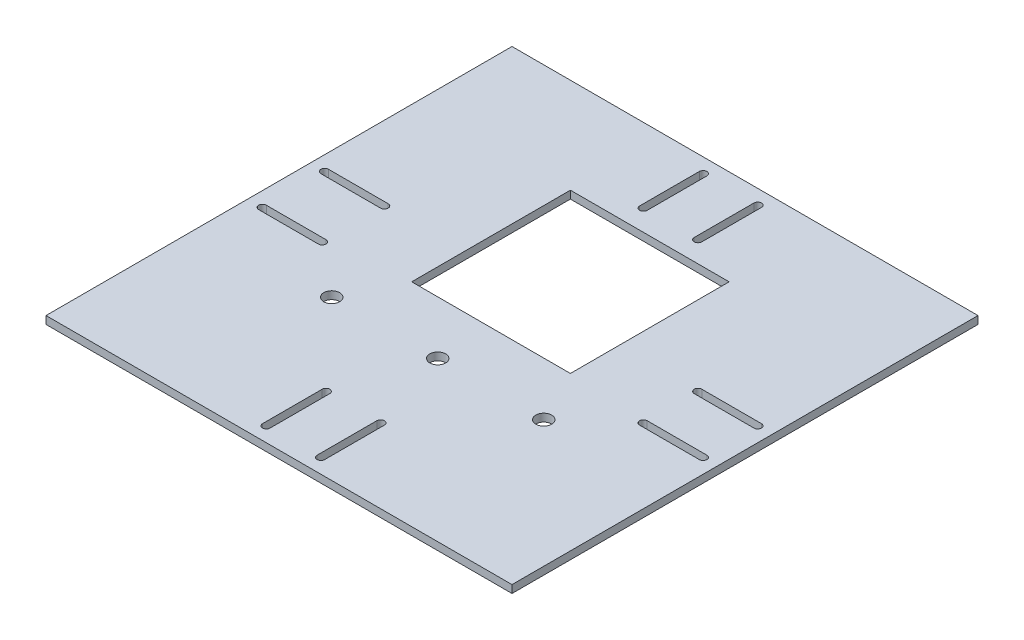
SolidWorks part; units mm, degrees
material "Acrylic (Medium-high impact)"
ref_plane "Front Plane" through (0, 0, 0) normal (0, 0, 1) x (1, 0, 0)
ref_plane "Top Plane" through (0, 0, 0) normal (0, 1, 0) x (1, 0, 0)
ref_plane "Right Plane" through (0, 0, 0) normal (1, 0, 0) x (0, 0, -1)
sketch "Sketch3" plane through (0, 0, 0) normal (0, 1, 0) x (1, 0, 0)
  line L1 (0, 0) -> (186.436, 0)
  line L2 (0, 0) -> (0, 186.436)
  line L3 (0, 186.436) -> (186.436, 186.436)
  line L4 (186.436, 0) -> (186.436, 186.436)
  dimension "D1" = 186.436
  dimension "D2" = 186.436
extrude "Boss-Extrude1" add sketch "Sketch3" along normal blind 3.0988
sketch "Sketch4" plane through (0, 3.0988, 0) normal (0, 1, 0) x (1, 0, 0)
  line L0 (5.842, 80.772) -> (29.718, 80.772) construction
  line L1 (5.842, 105.664) -> (29.718, 105.664) construction
  line L2 (5.842, 80.772) -> (5.842, 105.664) construction
  line L3 (29.718, 105.664) -> (29.718, 80.772) construction
  line L4 (0, 186.436) -> (0, 0) construction
  line L5 (0, 0) -> (186.436, 0) construction
  line L6 (186.436, 186.436) -> (0, 186.436) construction
  line L7 (5.842, 82.296) -> (29.718, 82.296)
  line L8 (5.842, 79.248) -> (29.718, 79.248)
  line L9 (5.842, 104.14) -> (29.718, 104.14)
  line L10 (5.842, 107.188) -> (29.718, 107.188)
  line L11 (186.436, 0) -> (186.436, 186.436) construction
  line L12 (82.296, 5.842) -> (82.296, 29.718) construction
  line L13 (82.296, 29.718) -> (104.14, 29.718) construction
  line L14 (104.14, 29.718) -> (104.14, 5.842) construction
  line L15 (104.14, 5.842) -> (82.296, 5.842) construction
  line L16 (80.772, 29.718) -> (80.772, 5.842)
  line L17 (83.82, 5.842) -> (83.82, 29.718)
  line L18 (105.664, 5.842) -> (105.664, 29.718)
  line L19 (156.718, 82.296) -> (180.594, 82.296) construction
  line L20 (156.718, 104.14) -> (180.594, 104.14) construction
  line L21 (156.718, 82.296) -> (156.718, 104.14) construction
  line L22 (180.594, 104.14) -> (180.594, 82.296) construction
  line L23 (156.718, 83.82) -> (180.594, 83.82)
  line L24 (156.718, 80.772) -> (180.594, 80.772)
  line L25 (156.718, 102.616) -> (180.594, 102.616)
  line L26 (156.718, 105.664) -> (180.594, 105.664)
  line L27 (102.616, 29.718) -> (102.616, 5.842)
  line L28 (82.296, 156.718) -> (82.296, 180.594) construction
  line L29 (82.296, 180.594) -> (104.14, 180.594) construction
  line L30 (104.14, 180.594) -> (104.14, 156.718) construction
  line L31 (104.14, 156.718) -> (82.296, 156.718) construction
  line L32 (80.772, 180.594) -> (80.772, 156.718)
  line L33 (83.82, 156.718) -> (83.82, 180.594)
  line L34 (105.664, 156.718) -> (105.664, 180.594)
  line L35 (102.616, 180.594) -> (102.616, 156.718)
  arc A0 (5.842, 82.296) -> (5.842, 79.248) centre (5.842, 80.772) ccw
  arc A1 (5.842, 107.188) -> (5.842, 104.14) centre (5.842, 105.664) ccw
  arc A2 (29.718, 104.14) -> (29.718, 107.188) centre (29.718, 105.664) ccw
  arc A3 (29.718, 79.248) -> (29.718, 82.296) centre (29.718, 80.772) ccw
  arc A4 (80.772, 5.842) -> (83.82, 5.842) centre (82.296, 5.842) ccw
  arc A5 (102.616, 5.842) -> (105.664, 5.842) centre (104.14, 5.842) ccw
  arc A6 (83.82, 29.718) -> (80.772, 29.718) centre (82.296, 29.718) ccw
  arc A7 (105.664, 29.718) -> (102.616, 29.718) centre (104.14, 29.718) ccw
  arc A8 (156.718, 83.82) -> (156.718, 80.772) centre (156.718, 82.296) ccw
  arc A9 (156.718, 105.664) -> (156.718, 102.616) centre (156.718, 104.14) ccw
  arc A10 (180.594, 102.616) -> (180.594, 105.664) centre (180.594, 104.14) ccw
  arc A11 (180.594, 80.772) -> (180.594, 83.82) centre (180.594, 82.296) ccw
  arc A12 (80.772, 156.718) -> (83.82, 156.718) centre (82.296, 156.718) ccw
  arc A13 (102.616, 156.718) -> (105.664, 156.718) centre (104.14, 156.718) ccw
  arc A14 (83.82, 180.594) -> (80.772, 180.594) centre (82.296, 180.594) ccw
  arc A15 (105.664, 180.594) -> (102.616, 180.594) centre (104.14, 180.594) ccw
  dimension "D1" = 3.048
  dimension "D2" = 3.048
  dimension "D3" = 3.048
  dimension "D4" = 3.048
  dimension "D9" = 80.772
  dimension "D10" = 80.772
  dimension "D11" = 5.842
  dimension "D12" = 29.718
  dimension "D13" = 3.048
  dimension "D14" = 3.048
  dimension "D15" = 3.048
  dimension "D16" = 3.048
  dimension "D17" = 3.048
  dimension "D18" = 3.048
  dimension "D19" = 3.048
  dimension "D20" = 3.048
  dimension "D25" = 3.048
  dimension "D5" = 5.842
  dimension "D6" = 80.772
  dimension "D7" = 80.772
  dimension "D8" = 29.718
  dimension "D21" = 80.772
  dimension "D22" = 80.772
  dimension "D23" = 5.842
  dimension "D24" = 29.718
  dimension "D26" = 80.772
  dimension "D27" = 80.772
  dimension "D28" = 5.842
  dimension "D29" = 29.718
extrude "Cut-Extrude1" cut sketch "Sketch4" against normal through all
sketch "Sketch5" plane through (0, 3.0988, 0) normal (0, 1, 0) x (1, 0, 0)
  line L0 (0, 186.436) -> (0, 0) construction
  line L1 (61.468, 148.336) -> (124.968, 148.336)
  line L2 (61.468, 148.336) -> (61.468, 84.836)
  line L3 (61.468, 84.836) -> (124.968, 84.836)
  line L4 (124.968, 148.336) -> (124.968, 84.836)
  line L5 (186.436, 186.436) -> (0, 186.436) construction
  line L6 (50.8, 63.5) -> (93.218, 63.5) construction
  line L7 (93.218, 63.5) -> (135.636, 63.5) construction
  line L8 (186.436, 0) -> (186.436, 186.436) construction
  line L9 (0, 0) -> (186.436, 0) construction
  circle A0 centre (50.8, 63.5) radius 3.175
  circle A1 centre (93.218, 63.5) radius 3.175
  circle A2 centre (135.636, 63.5) radius 3.175
  dimension "D5" = 6.35
  dimension "D6" = 6.35
  dimension "D7" = 6.35
  dimension "D1" = 63.5
  dimension "D2" = 63.5
  dimension "D3" = 61.468
  dimension "D4" = 38.1
  dimension "D8" = 50.8
  dimension "D9" = 50.8
  dimension "D10" = 63.5
extrude "Cut-Extrude2" cut sketch "Sketch5" against normal up to next
